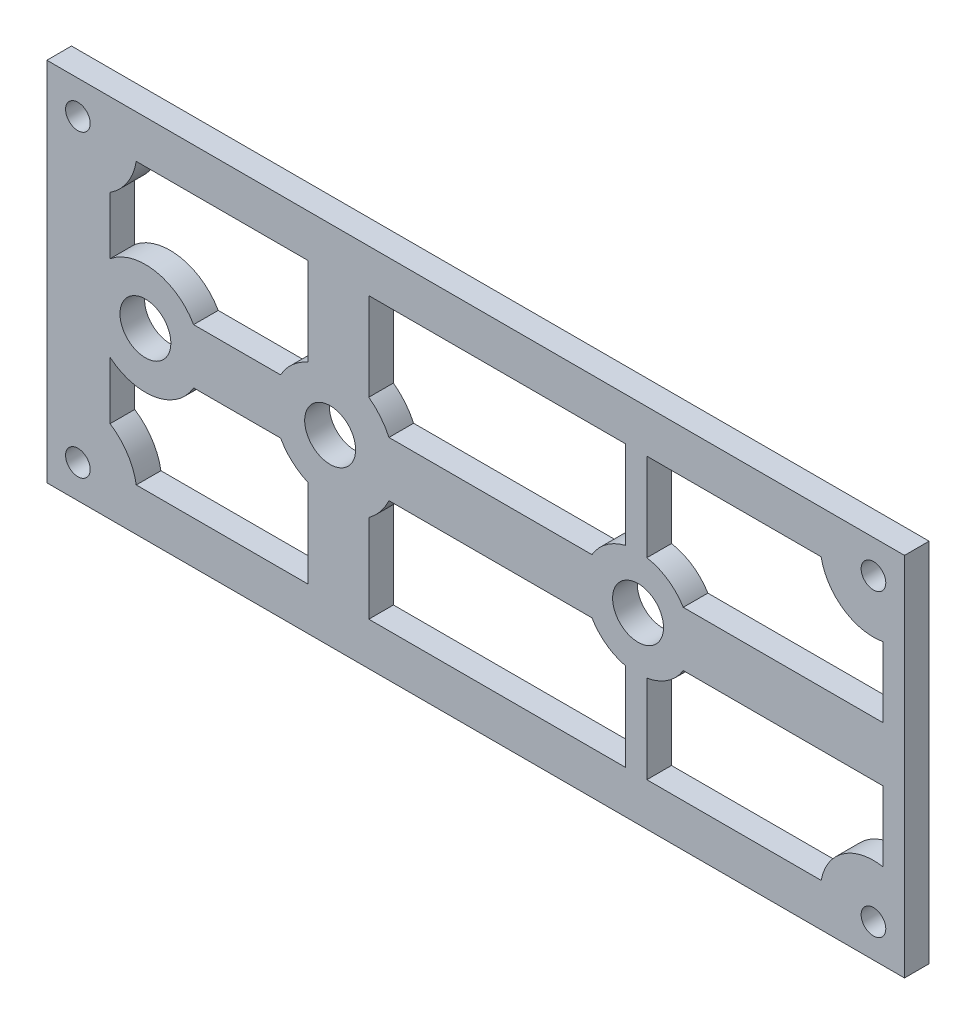
SolidWorks part; units mm, degrees
ref_plane "Front Plane" through (0, 0, 0) normal (0, 0, 1) x (1, 0, 0)
ref_plane "Top Plane" through (0, 0, 0) normal (0, 1, 0) x (1, 0, 0)
ref_plane "Right Plane" through (0, 0, 0) normal (1, 0, 0) x (0, 0, -1)
sketch "Sketch1" plane through (0, 0, 0) normal (0, 0, 1) x (1, 0, 0)
  line L1 (52.2249, -22.2885) -> (-52.2249, -22.2885)
  line L2 (52.2249, -22.2885) -> (52.2249, 22.2885)
  line L3 (52.2249, 22.2885) -> (-52.2249, 22.2885)
  line L4 (-52.2249, -22.2885) -> (-52.2249, 22.2885)
  line L5 (52.2249, -22.2885) -> (-52.2249, 22.2885) construction
  line L6 (52.2249, 22.2885) -> (-52.2249, -22.2885) construction
  point P0 (0, 0)
extrude "Boss-Extrude1" add sketch "Sketch1" along normal blind 3
sketch "Sketch3" plane through (0, 0, 3) normal (0, 0, 1) x (1, 0, 0)
  line L2 (-52.2249, 22.2885) -> (-52.2249, -22.2885) construction
  line L4 (52.2249, -22.2885) -> (52.2249, 22.2885) construction
  line L5 (-52.2249, 0) -> (52.2249, 0) construction
  circle A0 centre (19.7751, 0) radius 3.1
  circle A1 centre (-17.7249, 0) radius 3.1
  circle A2 centre (-40.2249, 0) radius 3.1
  dimension "D1" = 6.2
  dimension "D2" = 6.2
  dimension "D3" = 6.2
  dimension "D4" = 12
  dimension "D6" = 22.5
  dimension "D7" = 37.5
extrude "Cut-Extrude1" cut sketch "Sketch3" against normal blind 10
sketch "Sketch4" plane through (0, 0, 3) normal (0, 0, 1) x (1, 0, 0)
  circle A0 centre (-48.4471, 18.2482) radius 1.5
  dimension "D1" = 3
extrude "Cut-Extrude2" cut sketch "Sketch4" against normal blind 10
mirror "Mirror1" about plane through (0, 0, 0) normal (1, 0, 0) of "Cut-Extrude2"
mirror "Mirror2" about plane through (0, 0, 0) normal (0, 1, 0) of "Mirror1", "Cut-Extrude2"
sketch "Sketch5" plane through (0, 0, 3) normal (0, 0, 1) x (1, 0, 0)
  line L0 (-41.3371, 17.0645) -> (-20.4138, 17.0645)
  line L1 (-20.4138, 17.0645) -> (-20.4138, 6.3454)
  line L2 (-23.7569, 3.3332) -> (-34.3563, 3.3332)
  line L3 (-44.5262, 5.201) -> (-44.5262, 12.2)
  arc A0 (-44.5262, 12.2) -> (-41.3371, 17.0645) centre (-48.4471, 18.2482) ccw
  arc A1 (-20.4138, 6.3454) -> (-23.7569, 3.3332) centre (-17.7249, 0) ccw
  arc A2 (-34.3563, 3.3332) -> (-44.5262, 5.201) centre (-40.2249, 0) ccw
extrude "Cut-Extrude3" cut sketch "Sketch5" against normal through all
mirror "Mirror3" about plane through (0, 0, 0) normal (0, 1, 0) of "Cut-Extrude3"
sketch "Sketch6" plane through (0, 0, 3) normal (0, 0, 1) x (1, 0, 0)
  line L0 (-13.0158, -17.0645) -> (-13.0158, -6.3454)
  line L1 (-23.7569, -3.3332) -> (28.8116, -3.3332) construction
  line L2 (-10.5605, -3.3332) -> (14.1578, -3.3332)
  line L3 (-20.4138, -6.3454) -> (45.5994, -6.3454) construction
  line L4 (18.2258, -6.3454) -> (18.2258, -17.0645)
  line L5 (18.2258, -17.0645) -> (-13.0158, -17.0645)
  arc A0 (-13.0158, -6.3454) -> (-10.5605, -3.3332) centre (-17.7249, 0) ccw
  arc A1 (14.1578, -3.3332) -> (18.2258, -6.3454) centre (19.7751, 0) ccw
extrude "Cut-Extrude4" cut sketch "Sketch6" against normal through all
mirror "Mirror4" about plane through (0, 0, 0) normal (0, 1, 0) of "Cut-Extrude4"
sketch "Sketch7" plane through (0, 0, 3) normal (0, 0, 1) x (1, 0, 0)
  line L0 (18.2258, -6.3454) -> (45.4618, -6.3454) construction
  line L1 (14.1578, -3.3332) -> (46.5909, -3.3332) construction
  line L2 (20.8457, -6.3454) -> (20.8457, -17.0645)
  line L3 (20.8457, -17.0645) -> (42.0746, -17.0645)
  line L4 (49.6308, -11.8757) -> (49.6308, -3.3332)
  line L5 (49.6308, -3.3332) -> (25.2796, -3.3332)
  arc A0 (25.2796, -3.3332) -> (20.8457, -6.3454) centre (19.7751, 0) cw
  arc A1 (42.0746, -17.0645) -> (49.6308, -11.8757) centre (48.4471, -18.2482) cw
extrude "Cut-Extrude5" cut sketch "Sketch7" against normal through all
mirror "Mirror5" about plane through (0, 0, 0) normal (0, 1, 0) of "Cut-Extrude5"
